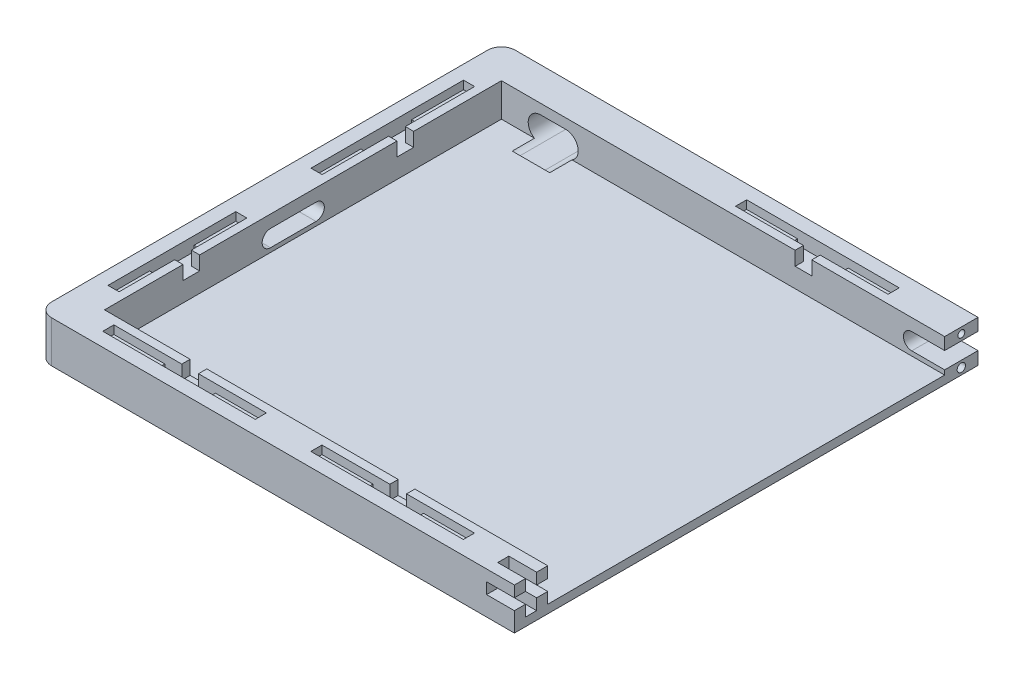
SolidWorks part; units mm, degrees
ref_plane "Front Plane" through (0, 0, 0) normal (0, 0, 1) x (1, 0, 0)
ref_plane "Top Plane" through (0, 0, 0) normal (0, 1, 0) x (1, 0, 0)
ref_plane "Right Plane" through (0, 0, 0) normal (1, 0, 0) x (0, 0, -1)
sketch "Sketch1" plane through (0, 0, 0) normal (0, 1, 0) x (1, 0, 0)
  line L0 (-131.0313, 0) -> (139.9056, 0) construction
  line L1 (0, 71.4375) -> (-159.54, 71.4375)
  line L2 (0, 215.1028) -> (0, -153.2812) construction
  line L3 (-159.54, 71.4375) -> (-159.54, -71.4375)
  line L4 (-159.54, -71.4375) -> (0, -71.4375)
  line L5 (0, 71.4375) -> (0, -71.4375)
  point P9 (0, 0)
  dimension "D1" = 159.54
  dimension "D2" = 142.875
extrude "Boss-Extrude1" add sketch "Sketch1" along normal blind 3
sketch "Sketch2" plane through (0, 0, 0) normal (0, 1, 0) x (1, 0, 0)
  line L0 (-224.2217, 0) -> (91.1792, 0) construction
  line L1 (0, 149.3369) -> (0, -151.0656) construction
  line L2 (0, 71.4375) -> (0, 83.4375)
  line L3 (0, 83.4375) -> (-171.54, 83.4375)
  line L4 (-171.54, 83.4375) -> (-171.54, -83.4375)
  line L5 (-171.54, -83.4375) -> (0, -83.4375)
  line L6 (0, -83.4375) -> (0, -71.4375)
  line L8 (-159.54, 71.4375) -> (-159.54, -71.4375) construction
  line L13 (0, -71.4375) -> (0, 71.4375)
  line L14 (0, 71.4375) -> (-159.54, 71.4375)
  line L15 (-159.54, 71.4375) -> (-159.54, -71.4375)
  line L16 (-159.54, -71.4375) -> (0, -71.4375)
  line L18 (0, 71.4375) -> (-159.54, 71.4375)
  line L19 (-159.54, 71.4375) -> (-159.54, -71.4375)
  line L20 (-159.54, -71.4375) -> (0, -71.4375)
  dimension "D1" = 12
  dimension "D2" = 12
  dimension "D3" = 12
  dimension "D4" = 0
extrude "Boss-Extrude2" add sketch "Sketch2" along normal blind 15
sketch "Sketch3" plane through (0, 15, 0) normal (0, 1, 0) x (1, 0, 0)
  line L0 (-159.54, 71.4375) -> (-159.54, 39.8375) construction
  line L1 (-159.54, -71.4375) -> (-159.54, 71.4375) construction
  line L2 (-159.54, -71.4375) -> (-159.54, -43.1875) construction
  line L3 (-159.54, 39.8375) -> (-159.54, 33.8375)
  line L4 (-159.54, 39.8375) -> (-162.54, 39.8375)
  line L5 (-159.54, 33.8375) -> (-162.54, 33.8375)
  line L6 (-162.54, 39.8375) -> (-162.54, 64.7884)
  line L7 (-162.54, 33.8375) -> (-162.54, 9.8884)
  line L8 (-162.54, 64.7884) -> (-166.54, 64.7884)
  line L9 (-166.54, 64.7884) -> (-166.54, 9.8884)
  line L10 (-166.54, 9.8884) -> (-162.54, 9.8884)
  line L11 (-159.54, 71.4375) -> (-159.54, -71.4375) construction
  line L12 (-23.37, -74.4375) -> (-47.82, -74.4375)
  line L13 (-159.54, -37.1875) -> (-159.54, -43.1875)
  line L14 (-159.54, -37.1875) -> (-162.54, -37.1875)
  line L15 (-159.54, -43.1875) -> (-162.54, -43.1875)
  line L16 (-162.54, -37.1875) -> (-162.54, -17.1875)
  line L17 (-162.54, -17.1875) -> (-166.54, -17.1875)
  line L18 (-166.54, -17.1875) -> (-166.54, -63.1875)
  line L19 (-166.54, -63.1875) -> (-162.54, -63.1875)
  line L20 (-162.54, -63.1875) -> (-162.54, -43.1875)
  line L21 (-23.37, -78.4375) -> (-23.37, -74.4375)
  line L22 (-78.27, -78.4375) -> (-23.37, -78.4375)
  line L23 (-78.27, -74.4375) -> (-78.27, -78.4375)
  line L24 (-53.82, -74.4375) -> (-78.27, -74.4375)
  line L25 (-53.82, -71.4375) -> (-53.82, -74.4375)
  line L26 (-47.82, -71.4375) -> (-53.82, -71.4375)
  line L27 (-47.82, -74.4375) -> (-47.82, -71.4375)
  line L28 (-98.27, -78.4375) -> (-98.27, -74.4375)
  line L29 (-153.17, -78.4375) -> (-98.27, -78.4375)
  line L30 (-153.17, -74.4375) -> (-153.17, -78.4375)
  line L31 (-128.72, -74.4375) -> (-153.17, -74.4375)
  line L32 (-128.72, -71.4375) -> (-128.72, -74.4375)
  line L33 (-122.72, -71.4375) -> (-128.72, -71.4375)
  line L34 (-122.72, -74.4375) -> (-122.72, -71.4375)
  line L35 (-98.27, -74.4375) -> (-122.72, -74.4375)
  line L36 (0, -71.4375) -> (-159.54, -71.4375) construction
  line L37 (-159.54, -71.4375) -> (0, -71.4375) construction
  line L38 (-47.82, 74.4375) -> (-47.82, 71.4375)
  line L39 (-23.37, 74.4375) -> (-47.82, 74.4375)
  line L40 (-23.37, 78.4375) -> (-23.37, 74.4375)
  line L41 (-78.27, 78.4375) -> (-23.37, 78.4375)
  line L42 (-78.27, 74.4375) -> (-78.27, 78.4375)
  line L43 (-53.82, 74.4375) -> (-78.27, 74.4375)
  line L44 (-53.82, 71.4375) -> (-53.82, 74.4375)
  line L45 (-47.82, 71.4375) -> (-53.82, 71.4375)
  line L46 (-159.54, 71.4375) -> (0, 71.4375) construction
  point P11 (-159.54, 36.8375)
  point P21 (-159.54, -40.1875)
  point P48 (0, 0)
  point P59 (0, 0)
  dimension "D1" = 31.6
  dimension "D2" = 54.9
  dimension "D3" = 6
  dimension "D4" = 3
  dimension "D5" = 6
  dimension "D6" = 20
  dimension "D7" = 4
  dimension "D8" = 4
  dimension "D9" = 28.25
  dimension "D10" = 3
  dimension "D11" = 30.82
  dimension "D12" = 6
  dimension "D13" = 3
  dimension "D14" = 4
  dimension "D15" = 54.9
  dimension "D16" = 68.9
  dimension "D17" = 6
  dimension "D18" = 3
  dimension "D19" = 4
  dimension "D20" = 54.9
  dimension "D21" = 6
  dimension "D22" = 3
  dimension "D23" = 4
  dimension "D24" = 54.9
  dimension "D25" = 47.82
extrude "Cut-Extrude1" cut sketch "Sketch3" against normal blind 3
sketch "Sketch4" plane through (0, 12, 0) normal (0, 1, 0) x (1, 0, 0)
  line L0 (-53.82, 74.4375) -> (-53.82, 71.4375)
  line L1 (-53.82, 71.4375) -> (-47.82, 71.4375)
  line L2 (-47.82, 71.4375) -> (-47.82, 74.4375)
  line L3 (-47.82, 74.4375) -> (-35.595, 74.4375) construction
  line L4 (-128.72, -74.4375) -> (-140.945, -74.4375) construction
  line L5 (-53.82, 74.4375) -> (-66.045, 74.4375) construction
  line L6 (-78.27, 74.4375) -> (-53.82, 74.4375) construction
  line L7 (-47.82, 74.4375) -> (-23.37, 74.4375) construction
  line L8 (-53.82, 74.4375) -> (-59.9325, 74.4375)
  line L9 (-59.9325, 74.4375) -> (-59.9325, 78.4375)
  line L10 (-23.37, 78.4375) -> (-78.27, 78.4375) construction
  line L11 (-59.9325, 78.4375) -> (-50.82, 78.4375)
  line L12 (-50.82, 78.4375) -> (-41.7075, 78.4375)
  line L13 (-41.7075, 78.4375) -> (-41.7075, 74.4375)
  line L14 (-47.82, 74.4375) -> (-41.7075, 74.4375)
  line L15 (-159.54, 39.8375) -> (-159.54, 33.8375)
  line L16 (-159.54, 33.8375) -> (-162.54, 33.8375)
  line L17 (-162.54, 39.8375) -> (-162.54, 52.313) construction
  line L18 (-162.54, 39.8375) -> (-162.54, 64.7884) construction
  line L19 (-162.54, 33.8375) -> (-162.54, 21.863) construction
  line L20 (-162.54, 9.8884) -> (-162.54, 33.8375) construction
  line L21 (-159.54, 39.8375) -> (-162.54, 39.8375)
  line L24 (-128.72, -74.4375) -> (-153.17, -74.4375) construction
  line L26 (-122.72, -74.4375) -> (-110.495, -74.4375) construction
  line L30 (-162.54, 39.8375) -> (-162.54, 46.0752)
  line L31 (-162.54, 46.0752) -> (-166.54, 46.0752)
  line L32 (-166.54, 64.7884) -> (-166.54, 9.8884) construction
  line L33 (-166.54, 46.0752) -> (-166.54, 27.8502)
  line L34 (-166.54, 64.7884) -> (-166.54, 9.8884) construction
  line L35 (-166.54, 27.8502) -> (-162.54, 27.8502)
  line L36 (-162.54, 27.8502) -> (-162.54, 33.8375)
  line L37 (-162.54, -37.1875) -> (-162.54, -27.1875) construction
  line L38 (-162.54, -37.1875) -> (-162.54, -17.1875) construction
  line L39 (-166.54, -32.1875) -> (-166.54, -48.1875)
  line L40 (-162.54, -63.1875) -> (-162.54, -43.1875) construction
  line L41 (-162.54, -32.1875) -> (-166.54, -32.1875)
  line L42 (-166.54, -17.1875) -> (-166.54, -63.1875) construction
  line L43 (-162.54, -43.1875) -> (-162.54, -53.1875) construction
  line L44 (-166.54, -48.1875) -> (-162.54, -48.1875)
  line L45 (-162.54, -48.1875) -> (-162.54, -43.1875)
  line L46 (-162.54, -43.1875) -> (-159.54, -43.1875)
  line L47 (-159.54, -43.1875) -> (-159.54, -37.1875)
  line L48 (-159.54, -37.1875) -> (-162.54, -37.1875)
  line L49 (-162.54, -37.1875) -> (-162.54, -32.1875)
  line L50 (-98.27, -74.4375) -> (-122.72, -74.4375) construction
  line L51 (-128.72, -71.4375) -> (-128.72, -74.4375)
  line L52 (-128.72, -74.4375) -> (-134.8325, -74.4375)
  line L53 (-134.8325, -74.4375) -> (-134.8325, -78.4375)
  line L54 (-153.17, -78.4375) -> (-98.27, -78.4375) construction
  line L55 (-134.8325, -78.4375) -> (-116.6075, -78.4375)
  line L56 (-116.6075, -78.4375) -> (-116.6075, -74.4375)
  line L59 (-122.72, -71.4375) -> (-128.72, -71.4375)
  line L60 (-122.72, -71.4375) -> (-122.72, -74.4375)
  line L61 (-122.72, -74.4375) -> (-116.6075, -74.4375)
  line L62 (-53.82, -74.4375) -> (-66.045, -74.4375) construction
  line L63 (-53.82, -74.4375) -> (-78.27, -74.4375) construction
  line L64 (-47.82, -74.4375) -> (-35.595, -74.4375) construction
  line L65 (-23.37, -74.4375) -> (-47.82, -74.4375) construction
  line L66 (-53.82, -74.4375) -> (-59.9325, -74.4375)
  line L67 (-59.9325, -74.4375) -> (-59.9325, -78.4375)
  line L68 (-78.27, -78.4375) -> (-23.37, -78.4375) construction
  line L69 (-59.9325, -78.4375) -> (-41.7075, -78.4375)
  line L70 (-41.7075, -78.4375) -> (-41.7075, -74.4375)
  line L71 (-41.7075, -74.4375) -> (-47.82, -74.4375)
  line L72 (-47.82, -74.4375) -> (-47.82, -71.4375)
  line L73 (-47.82, -71.4375) -> (-53.82, -71.4375)
  line L74 (-53.82, -71.4375) -> (-53.82, -74.4375)
extrude "Cut-Extrude2" cut sketch "Sketch4" against normal blind 2
sketch "Sketch5" plane through (-171.54, 0, 0) normal (-1, 0, 0) x (0, 0, 1)
  line L0 (0, 7.5) -> (32.6582, 7.5) construction
  line L1 (-83.4375, 7.5) -> (0, 7.5) construction
  line L2 (-83.4375, 15) -> (-83.4375, 0) construction
  line L3 (-83.4375, 11.8257) -> (-7.6875, 11.8257) construction
  line L4 (-4.6875, 10.5) -> (11.6925, 10.5)
  line L5 (-4.6875, 4.5) -> (11.6925, 4.5)
  line L8 (-7.6875, 4.845) -> (-7.6875, 10.155) construction
  arc A0 (-4.6875, 4.5) -> (-4.6875, 10.5) centre (-4.6875, 7.5) cw
  arc A1 (11.6925, 10.5) -> (11.6925, 4.5) centre (11.6925, 7.5) cw
  point P12 (3.5025, 10.5)
  point P13 (3.5025, 4.5)
  point P17 (-4.6875, 10.5)
  point P21 (-7.6875, 7.5)
  dimension "D2" = 3
  dimension "D1" = 16.38
  dimension "D3" = 75.75
extrude "Cut-Extrude3" cut sketch "Sketch5" against normal blind 12
sketch "Sketch7" plane through (0, 0, -83.4375) normal (0, 0, -1) x (-1, 0, 0)
  line L0 (60.062, 7.6343) -> (-60.062, 7.6343) construction
  line L2 (14.8425, 7.6343) -> (14.8425, 12.6467) construction
  line L3 (-4.5375, 10.6343) -> (11.8425, 10.6343)
  line L4 (-4.5375, 4.6343) -> (11.8425, 4.6343)
  line L5 (0, 11.4722) -> (14.8425, 11.4722) construction
  line L6 (0, 15) -> (0, 0) construction
  arc A0 (-4.5375, 4.6343) -> (-4.5375, 10.6343) centre (-4.5375, 7.6343) cw
  arc A1 (11.8425, 10.6343) -> (11.8425, 4.6343) centre (11.8425, 7.6343) cw
  point P3 (0, 7.6343)
  dimension "D3" = 3
  dimension "D1" = 14.8425
  dimension "D2" = 16.38
extrude "Cut-Extrude5" cut sketch "Sketch7" against normal blind 12
sketch "Sketch8" plane through (0, 0, -83.4375) normal (0, 0, -1) x (-1, 0, 0)
  line L0 (171.54, 7.5) -> (143.1877, 7.5) construction
  line L1 (171.54, 15) -> (171.54, 0) construction
  line L2 (171.54, 7.9) -> (145.4, 7.9) construction
  line L3 (145.4, 7.9) -> (136.4, 7.9) construction
  line L4 (0, 15) -> (171.54, 15) construction
  line L5 (136.4, 11.4) -> (145.4, 11.4)
  line L6 (136.4, 2.4) -> (145.4, 2.4)
  line L7 (164.2575, 6.9) -> (140.1095, 6.9) construction
  line L8 (140.9, 7.9) -> (140.9, 5.9) construction
  line L9 (145.4, 7.9) -> (145.4, 15.4665) construction
  arc A0 (136.4, 2.4) -> (136.4, 11.4) centre (136.4, 6.9) cw
  arc A1 (145.4, 11.4) -> (145.4, 2.4) centre (145.4, 6.9) cw
  point P19 (140.9, 6.9)
  point P20 (0, 0)
  dimension "D5" = 9
  dimension "D1" = 26.14
  dimension "D2" = 9
  dimension "D3" = 7.1
  dimension "D4" = 9
  dimension "D6" = 1
  dimension "2" = 2
extrude "Cut-Extrude6" cut sketch "Sketch8" against normal blind 20
sketch "Sketch9" plane through (-159.54, 0, 0) normal (1, 0, 0) x (0, 0, -1)
  line L0 (0, 4.5) -> (0, 3) construction
  line L1 (4.6875, 4.5) -> (-11.6925, 4.5) construction
  line L2 (71.4375, 3) -> (-71.4375, 3) construction
  line L3 (36.8375, 10) -> (36.8375, 3) construction
  line L4 (33.8375, 10) -> (39.8375, 10) construction
sketch "Sketch10" plane through (0, 0, 0) normal (1, 0, 0) x (0, 0, -1)
  line L0 (-71.4375, 3) -> (-71.4375, 15) construction
  line L1 (-71.4375, 15) -> (-83.4375, 15) construction
  line L2 (-83.4375, 15) -> (-83.4375, 3) construction
  line L3 (-83.4375, 15) -> (-83.4375, 0) construction
  line L4 (-83.4375, 3) -> (-71.4375, 3) construction
  line L5 (-71.4375, 3) -> (-83.4375, 15) construction
  line L6 (-83.4375, 15) -> (-71.4375, 15) construction
  line L7 (-71.4375, 15) -> (-83.4375, 3) construction
  line L8 (-77.4375, 15.3824) -> (-77.4375, 3) construction
  line L9 (-83.4375, 9) -> (-71.292, 9) construction
  line L10 (-79.4375, 15) -> (-75.4375, 15)
  line L11 (-71.4375, 7) -> (-71.4375, 11)
  line L12 (-75.4375, 3) -> (-79.4375, 3)
  line L13 (-83.4375, 7) -> (-83.4375, 11)
  line L14 (-79.4375, 15) -> (-79.4375, 11)
  line L15 (-79.4375, 11) -> (-83.4375, 11)
  line L16 (-83.4375, 7) -> (-79.4375, 7)
  line L17 (-79.4375, 7) -> (-79.4375, 3)
  line L18 (-75.4375, 3) -> (-75.4375, 7)
  line L19 (-75.4375, 7) -> (-71.4375, 7)
  line L20 (-71.4375, 11) -> (-75.4375, 11)
  line L21 (-75.4375, 11) -> (-75.4375, 15)
  line L22 (-77.4375, 9) -> (-77.4375, 15) construction
  line L23 (-71.4375, 9) -> (-83.4375, 9) construction
  point P15 (-77.4375, 15)
  point P19 (-71.4375, 9)
  point P22 (-77.4375, 3)
  point P25 (-83.4375, 9)
  dimension "D1" = 4
  dimension "D2" = 4
  dimension "D3" = 4
  dimension "D4" = 4
  dimension "D5" = 0
extrude "Cut-Extrude8" cut sketch "Sketch10" against normal blind 10
fillet "Fillet2" radius 5 1 edges at (-171.54, 7.5, 83.4375)
fillet "Fillet3" radius 5 1 edges at (-171.54, 7.5, -83.4375)
sketch "Sketch11" plane through (0, 0, 0) normal (1, 0, 0) x (0, 0, -1)
  line L0 (71.4375, 4.6343) -> (83.4375, 4.6343) construction
  line L1 (71.4375, 4.6343) -> (71.4375, 0) construction
  line L2 (-83.4375, 0) -> (83.4375, 0) construction
  line L3 (71.4375, 0) -> (83.4375, 0) construction
  line L4 (83.4375, 0) -> (83.4375, 4.6343) construction
  line L5 (77.4375, 4.6343) -> (77.4375, 0) construction
  line L6 (71.4375, 2.3172) -> (83.4375, 2.3172) construction
  line L7 (71.4375, 15) -> (71.4375, 10.6343) construction
  line L8 (71.4375, 10.6343) -> (83.4375, 10.6343) construction
  line L9 (83.4375, 10.6343) -> (83.4375, 15) construction
  line L10 (83.4375, 15) -> (71.4375, 15) construction
  line L11 (71.4375, 15) -> (77.4375, 15) construction
  line L12 (77.4375, 15) -> (77.4375, 10.6343) construction
  line L13 (77.4375, 10.6343) -> (71.4375, 10.6343) construction
  line L14 (71.4375, 10.6343) -> (71.4375, 12.8172) construction
  line L15 (71.4375, 12.8172) -> (83.4375, 12.8172) construction
  circle A0 centre (77.4375, 2.3172) radius 1.5
  circle A1 centre (77.4375, 12.8172) radius 1.25
  dimension "D1" = 3
  dimension "D2" = 2.5
extrude "Cut-Extrude9" cut sketch "Sketch11" against normal blind 10
